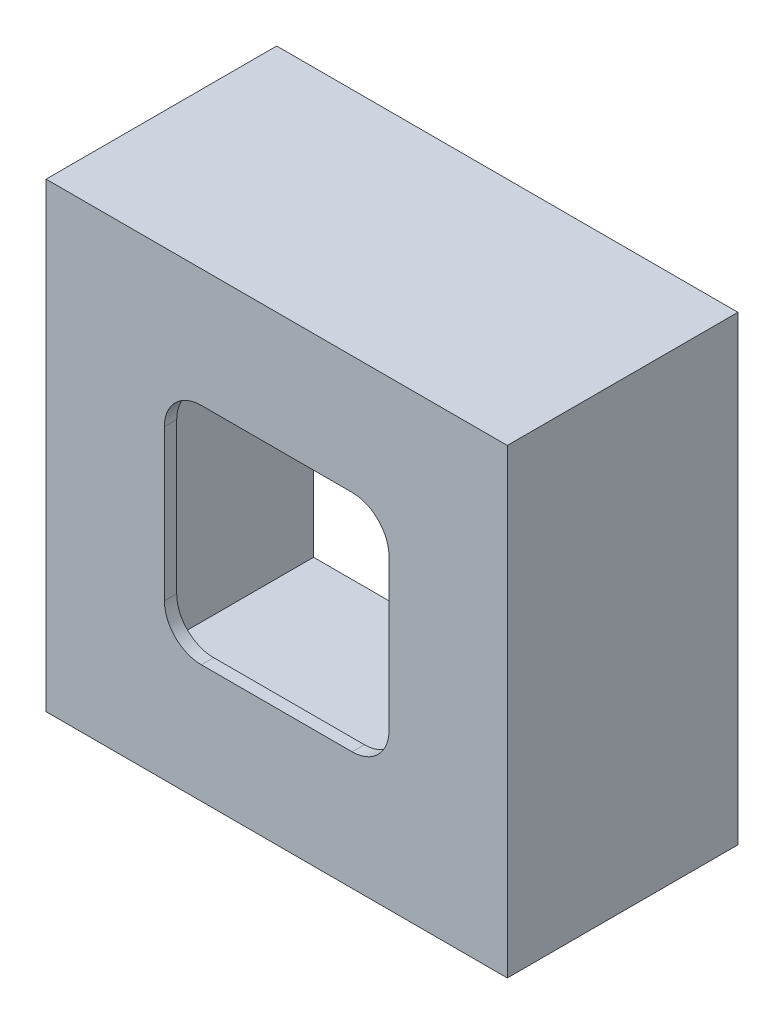
SolidWorks part; units mm, degrees
ref_plane "Front Plane" through (0, 0, 0) normal (0, 0, 1) x (1, 0, 0)
ref_plane "Top Plane" through (0, 0, 0) normal (0, 1, 0) x (1, 0, 0)
ref_plane "Right Plane" through (0, 0, 0) normal (1, 0, 0) x (0, 0, -1)
sketch "Sketch1" plane through (0, 0, 0) normal (0, 0, 1) x (1, 0, 0)
  line L4 (12.2635, 18.2635) -> (-12.2635, 18.2635)
  line L5 (18.2635, -12.2635) -> (18.2635, 12.2635)
  line L6 (-12.2635, -18.2635) -> (12.2635, -18.2635)
  line L7 (-18.2635, 12.2635) -> (-18.2635, -12.2635)
  line L8 (-35.5, 35.5) -> (-35.5, -35.5) construction
  line L9 (37.5, 37.5) -> (-37.5, 37.5)
  line L10 (37.5, 37.5) -> (37.5, -37.5)
  line L11 (37.5, -37.5) -> (-37.5, -37.5)
  line L12 (-37.5, 37.5) -> (-37.5, -37.5)
  line L13 (37.5, 37.5) -> (-37.5, -37.5) construction
  line L14 (37.5, -37.5) -> (-37.5, 37.5) construction
  line L15 (35.5, 35.5) -> (-35.5, 35.5) construction
  line L16 (-18.2635, 12.2635) -> (-18.2635, -12.2635) construction
  line L20 (12.2635, 18.2635) -> (-12.2635, 18.2635) construction
  line L21 (18.2635, -12.2635) -> (18.2635, 12.2635) construction
  line L22 (-12.2635, -18.2635) -> (12.2635, -18.2635) construction
  arc A4 (-12.2635, 18.2635) -> (-18.2635, 12.2635) centre (-12.2635, 12.2635) ccw
  arc A5 (18.2635, 12.2635) -> (12.2635, 18.2635) centre (12.2635, 12.2635) ccw
  arc A6 (12.2635, -18.2635) -> (18.2635, -12.2635) centre (12.2635, -12.2635) ccw
  arc A7 (-18.2635, -12.2635) -> (-12.2635, -18.2635) centre (-12.2635, -12.2635) ccw
  arc A10 (18.2635, 12.2635) -> (12.2635, 18.2635) centre (12.2635, 12.2635) ccw construction
  arc A11 (-12.2635, 18.2635) -> (-18.2635, 12.2635) centre (-12.2635, 12.2635) ccw construction
  arc A12 (12.2635, -18.2635) -> (18.2635, -12.2635) centre (12.2635, -12.2635) ccw construction
  arc A13 (-18.2635, -12.2635) -> (-12.2635, -18.2635) centre (-12.2635, -12.2635) ccw construction
  point P4 (0, 0)
  dimension "D1" = 2
  dimension "D2" = 2
extrude "Boss-Extrude1" add sketch "Sketch1" against normal up to surface (2 mm away)
sketch "Sketch2" plane through (0, 0, -2) normal (0, 0, -1) x (-1, 0, 0)
  line L5 (-37.5, 37.5) -> (37.5, 37.5)
  line L6 (-37.5, 37.5) -> (-37.5, -37.5)
  line L7 (-37.5, -37.5) -> (37.5, -37.5)
  line L8 (37.5, 37.5) -> (37.5, -37.5)
  line L9 (-31.5, 31.5) -> (31.5, 31.5)
  line L10 (-31.5, 31.5) -> (-31.5, -31.5)
  line L11 (-31.5, -31.5) -> (31.5, -31.5)
  line L12 (31.5, 31.5) -> (31.5, -31.5)
extrude "Boss-Extrude2" add sketch "Sketch2" along normal blind 35.5
